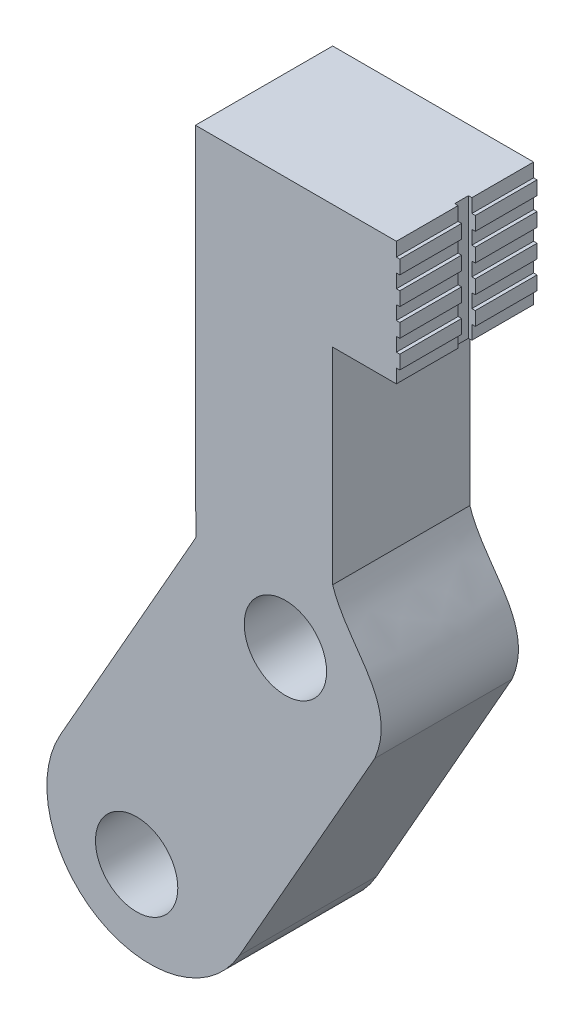
SolidWorks part; units mm, degrees
ref_plane "Front Plane" through (0, 0, 0) normal (0, 0, 1) x (1, 0, 0)
ref_plane "Top Plane" through (0, 0, 0) normal (0, 1, 0) x (1, 0, 0)
ref_plane "Right Plane" through (0, 0, 0) normal (1, 0, 0) x (0, 0, -1)
sketch "Sketch1" plane through (0, 0, 0) normal (0, 0, 1) x (1, 0, 0)
  line L0 (0, 0) -> (-9.8808, -17.3888)
  line L4 (0, 0) -> (-0.0344, 5)
  line L5 (-0.0344, 5) -> (-0.0344, 15)
  line L8 (9.9656, 17) -> (9.9656, 2)
  line L9 (3.1608, -24.7994) -> (13.0416, -7.4106)
  line L10 (-0.0344, 15) -> (-0.0344, 26)
  line L12 (9.9656, 17) -> (14.8568, 17)
  line L13 (-0.0344, 26) -> (14.8568, 26)
  line L14 (14.8568, 26) -> (14.8568, 17)
  arc A0 (3.1608, -24.7994) -> (-9.8808, -17.3888) centre (-3.36, -21.0941) cw
  spline S0 degree 3 poles (13.0416, -7.4106) (14.8063, -3.2033) (10.9918, -1.2618) (9.9656, 2) knots 0 0 0 0 1 1 1 1
  dimension "D1" = 15
  dimension "D2" = 15
  dimension "D3" = 20
  dimension "D4" = 20
  dimension "D5" = 150
  dimension "D6" = 10
  dimension "D7" = 5
  dimension "D8" = 9
extrude "Boss-Extrude1" add sketch "Sketch1" along normal blind 10
sketch "Sketch2" plane through (14.8568, 0, 0) normal (1, 0, 0) x (0, 0, -1)
  line L0 (0, 17) -> (0, 26) construction
  line L1 (-10, 25) -> (0, 25)
  line L2 (-10, 17) -> (-10, 26) construction
  line L3 (-10, 24) -> (0, 24)
  line L4 (-10, 23) -> (0, 23)
  line L5 (-10, 22) -> (0, 22)
  line L6 (-10, 20) -> (0, 20)
  line L7 (-10, 19) -> (0, 19)
  line L8 (-10, 18) -> (0, 18)
  line L9 (-10, 18) -> (0, 18)
  line L10 (-10, 26) -> (0, 26) construction
  line L11 (-10, 17) -> (0, 17) construction
  line L12 (-10, 26) -> (-10, 17)
  line L13 (-10, 26) -> (0, 26)
  line L14 (0, 26) -> (0, 17)
  line L15 (-10, 21) -> (0, 21)
  line L16 (-5, 26) -> (-5, 17)
  line L17 (-10, 17) -> (0, 17) construction
  line L18 (-5.5, 26) -> (-5.5, 17)
  line L19 (-4.5, 26) -> (-4.5, 17)
  line L20 (-5.5, 17) -> (-4.5, 17)
  line L21 (-5.5, 26) -> (-4.5, 26)
  line M9 (0, 17) -> (0, 26)
  line M11 (-10, 26) -> (-10, 17)
  line M12 (-10, 17) -> (0, 17)
  dimension "D1" = 1
  dimension "D2" = 1
  dimension "D3" = 1
  dimension "D4" = 1
  dimension "D5" = 1
  dimension "D6" = 1
  dimension "D7" = 1
  dimension "D8" = 1
  dimension "D9" = 0.5
  dimension "D10" = 0.5
extrude "Cut-Extrude1" cut sketch "Sketch2" against normal blind 0.5 contours L3 L1 M11 M9 | L5 L4 M11 M9 | L15 L12 L6 M9 | L8 L7 M11 M9 | L19 L7 L16 L9 | L19 L9 L16 M12 | L9 L18 L16 M12 | L6 L18 L7 L16 | L19 L6 L16 L7 | L19 L15 L16 L6 | L19 L5 L16 L15 | L5 L18 L15 L16 | L19 L4 L16 L5 | L19 L3 L16 L4 | L3 L18 L4 L16 | L19 L1 L16 L3 | L19 L13 L16 L1 | L13 L18 L1 L16
sketch "Sketch4" plane through (14.8568, 0, 0) normal (1, 0, 0) x (0, 0, -1)
  line L0 (-10, 25) -> (0, 25)
  line L1 (-10, 17) -> (-10, 26) construction
  line L2 (0, 17) -> (0, 26) construction
  line L3 (-10, 24) -> (0, 24)
  line L4 (-10, 23) -> (0, 23)
  line L5 (-10, 21) -> (0, 21)
  line L6 (-10, 22) -> (0, 22)
  line L7 (-10, 20) -> (0, 20)
  line L8 (-10, 19) -> (0, 19)
  line L9 (-10, 18) -> (0, 18)
  line L10 (-10, 17) -> (0, 17)
  line L11 (-4.5, 26) -> (0, 26) construction
  line M9 (-10, 17) -> (-5.5, 17)
  line M10 (-5.5, 17) -> (-5.5, 26)
  line M11 (-5.5, 26) -> (-10, 26)
  line M12 (-10, 26) -> (-10, 17)
  dimension "D1" = 1
  dimension "D2" = 1
  dimension "D3" = 1
  dimension "D4" = 1
  dimension "D5" = 1
  dimension "D6" = 1
  dimension "D7" = 1
  dimension "D8" = 1
extrude "Cut-Extrude4" cut sketch "Sketch4" against normal blind 0.25 contours L9 M12 M9 M10 | L8 L7 M12 M10 | L6 L5 M12 M10 | L4 L3 M12 M10 | L0 M12 M10 M11
sketch "Sketch5" plane through (14.8568, 0, 0) normal (1, 0, 0) x (0, 0, -1)
  line L0 (-5.5, 25) -> (0, 25)
  line L1 (0, 17) -> (0, 26) construction
  line L2 (-5.5, 24) -> (0, 24)
  line L3 (-5.5, 23) -> (0, 23)
  line L4 (-5.5, 18) -> (0, 18)
  line L5 (-5.5, 19) -> (0, 19)
  line L6 (-5.5, 20) -> (0, 20)
  line L7 (-5.5, 21) -> (0, 21)
  line L8 (-5.5, 22) -> (0, 22)
  line L9 (-4.5, 26) -> (-4.5, 17)
  line M1 (-4.5, 26) -> (-4.5, 17)
  line M2 (-4.5, 17) -> (0, 17)
  line M3 (0, 17) -> (0, 26)
  line M4 (0, 26) -> (-4.5, 26)
extrude "Cut-Extrude5" cut sketch "Sketch5" against normal blind 0.25 contours L4 M1 M2 M3 | L6 L5 M1 M3 | L8 L7 M1 M3 | L3 L2 M1 M3 | L0 M1 M3 M4
sketch "Sketch6" plane through (0, 0, 10) normal (0, 0, 1) x (1, 0, 0)
  line L0 (0, 0) -> (-9.8808, -17.3888) construction
  line L2 (-4.3194, -22.7826) -> (9.9656, 2)
  line L3 (0, 0) -> (13.0416, -7.4106)
  circle A0 centre (-4.3194, -22.7826) radius 3
  circle A2 centre (6.5208, -3.7053) radius 3
  dimension "D1" = 6
  dimension "D2" = 6
  dimension "D3" = 7.5
extrude "Cut-Extrude6" cut sketch "Sketch6" against normal through all
